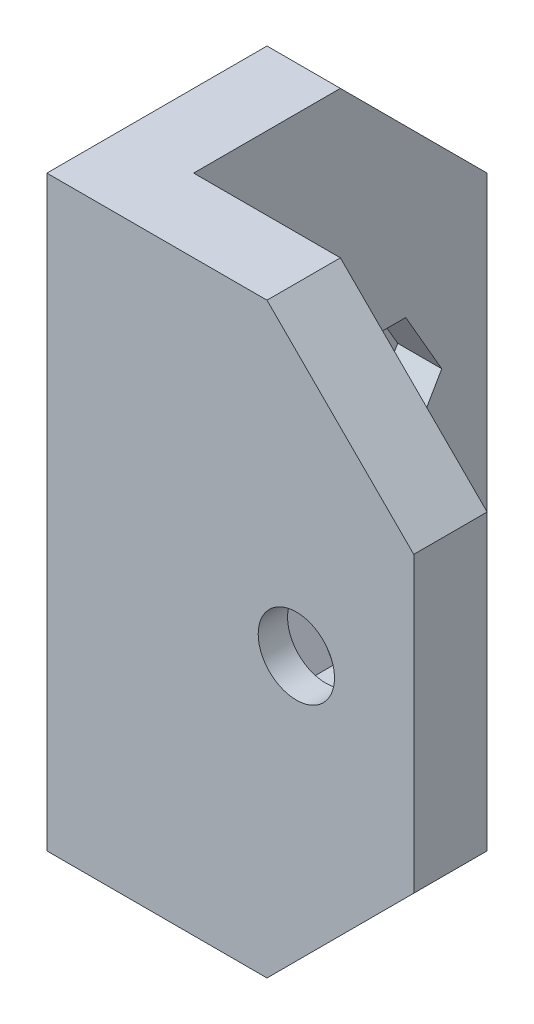
SolidWorks part; units mm, degrees
ref_plane "Front Plane" through (0, 0, 0) normal (0, 0, 1) x (1, 0, 0)
ref_plane "Top Plane" through (0, 0, 0) normal (0, 1, 0) x (1, 0, 0)
ref_plane "Right Plane" through (0, 0, 0) normal (1, 0, 0) x (0, 0, -1)
sketch "Sketch1" plane through (0, 0, 0) normal (0, 1, 0) x (1, 0, 0)
  line L0 (0, 0) -> (25, 0)
  line L1 (25, 0) -> (25, 5)
  line L2 (25, 5) -> (5, 5)
  line L3 (5, 5) -> (5, 25)
  line L4 (5, 25) -> (0, 25)
  line L5 (0, 25) -> (0, 0)
  dimension "D1" = 5
  dimension "D2" = 5
  dimension "D3" = 20
  dimension "D4" = 20
extrude "Boss-Extrude1" add sketch "Sketch1" along normal blind 40
sketch "Sketch2" plane through (0, 0, -5) normal (0, 0, -1) x (-1, 0, 0)
  line L0 (0, 40) -> (0, 0) construction
  line L1 (0, 20) -> (-25, 20) construction
  line L2 (-25, 40) -> (-25, 0) construction
  circle A0 centre (-17, 20) radius 2.6
  point P8 (0, 0)
  dimension "D1" = 17
  dimension "D2" = 5.2
extrude "Cut-Extrude1" cut sketch "Sketch2" against normal blind 40
sketch "Sketch3" plane through (0, 0, -5) normal (0, 0, -1) x (-1, 0, 0)
  line L0 (-25, 40) -> (-25, 0) construction
  line L1 (-14.5463, 24.25) -> (-19.4537, 24.25)
  line L2 (-19.4537, 24.25) -> (-21.9075, 20)
  line L3 (-21.9075, 20) -> (-19.4537, 15.75)
  line L4 (-19.4537, 15.75) -> (-14.5463, 15.75)
  line L5 (-14.5463, 15.75) -> (-12.0925, 20)
  line L6 (-12.0925, 20) -> (-14.5463, 24.25)
  circle A0 centre (-17, 20) radius 4.25 construction
  dimension "D1" = 8.5
extrude "Cut-Extrude2" cut sketch "Sketch3" against normal offset from surface (3 mm away) 2 up to face at (14.4, 20, 0)
sketch "Sketch4" plane through (5, 0, 0) normal (1, 0, 0) x (0, 0, -1)
  line L0 (0, 20) -> (25, 20) construction
  line L1 (0, 40) -> (0, 0) construction
  line L2 (25, 40) -> (25, 0) construction
  circle A0 centre (17, 20) radius 2.6
  dimension "D1" = 17
  dimension "D2" = 5.2
extrude "Cut-Extrude3" cut sketch "Sketch4" against normal through all both and the other way through all
sketch "Sketch5" plane through (5, 0, 0) normal (1, 0, 0) x (0, 0, -1)
  line L0 (25, 40) -> (25, 0) construction
  line L1 (19.4537, 24.25) -> (14.5463, 24.25)
  line L2 (14.5463, 24.25) -> (12.0925, 20)
  line L3 (12.0925, 20) -> (14.5463, 15.75)
  line L4 (14.5463, 15.75) -> (19.4537, 15.75)
  line L5 (19.4537, 15.75) -> (21.9075, 20)
  line L6 (21.9075, 20) -> (19.4537, 24.25)
  circle A0 centre (17, 20) radius 4.25 construction
  dimension "D1" = 8.5
extrude "Cut-Extrude4" cut sketch "Sketch5" against normal offset from surface (3 mm away) 2 up to face at (0, 20, -19.6)
chamfer "Chamfer1" distance 10 angle 45 4 edges at (25, 0, -2.5) (25, 40, -2.5) (2.5, 0, -25) (2.5, 40, -25)
